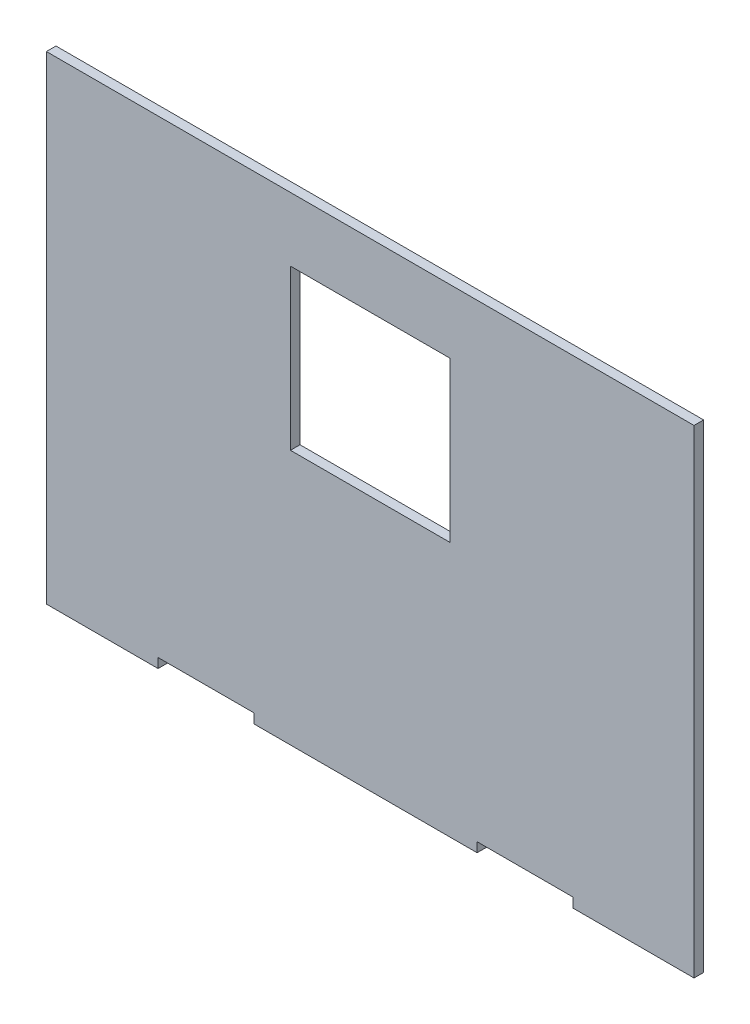
SolidWorks part; units mm, degrees
ref_plane "Front Plane" through (0, 0, 0) normal (0, 0, 1) x (1, 0, 0)
ref_plane "Top Plane" through (0, 0, 0) normal (0, 1, 0) x (1, 0, 0)
ref_plane "Right Plane" through (0, 0, 0) normal (1, 0, 0) x (0, 0, -1)
sketch "Sketch1" plane through (0, 0, 0) normal (0, 0, 1) x (1, 0, 0)
  line L1 (-101.5, 75) -> (101.5, 75)
  line L2 (-101.5, 75) -> (-101.5, -75)
  line L3 (-101.5, -75) -> (101.5, -75)
  line L4 (101.5, 75) -> (101.5, -75)
  line L5 (-101.5, 75) -> (101.5, -75) construction
  line L6 (-101.5, -75) -> (101.5, 75) construction
  point P0 (0, 0)
  dimension "D1" = 150
  dimension "D2" = 203
extrude "Boss-Extrude1" add sketch "Sketch1" along normal blind 3
sketch "Sketch2" plane through (0, 0, 3) normal (0, 0, 1) x (1, 0, 0)
  line L0 (0, 0) -> (0, 75) construction
  line L1 (101.5, 75) -> (-101.5, 75) construction
  line L3 (-25, 55) -> (25, 55)
  line L4 (-25, 55) -> (-25, 5)
  line L5 (-25, 5) -> (25, 5)
  line L6 (25, 55) -> (25, 5)
  line L7 (-25, 55) -> (25, 5) construction
  line L8 (-25, 5) -> (25, 55) construction
  dimension "D1" = 50
  dimension "D2" = 50
  dimension "D3" = 20
extrude "Cut-Extrude1" cut sketch "Sketch2" against normal blind 10
sketch "Sketch3" plane through (0, 0, 3) normal (0, 0, 1) x (1, 0, 0)
  line L0 (-101.5, -75) -> (101.5, -75) construction
  line L1 (-66.5, -75) -> (-36.5, -75)
  line L2 (-66.5, -75) -> (-66.5, -72)
  line L3 (-66.5, -72) -> (-36.5, -72)
  line L4 (-36.5, -75) -> (-36.5, -72)
  line L5 (-51.5, -75) -> (-51.5, -72) construction
  line L6 (-101.5, 75) -> (-101.5, -75) construction
  line L7 (33.5, -75) -> (33.5, -72)
  line L8 (33.5, -75) -> (63.5, -75)
  line L9 (63.5, -75) -> (63.5, -72)
  line L10 (33.5, -72) -> (63.5, -72)
  dimension "D1" = 30
  dimension "D2" = 3
  dimension "D3" = 50
  dimension "D4" = 2
extrude "Cut-Extrude2" cut sketch "Sketch3" against normal blind 10
